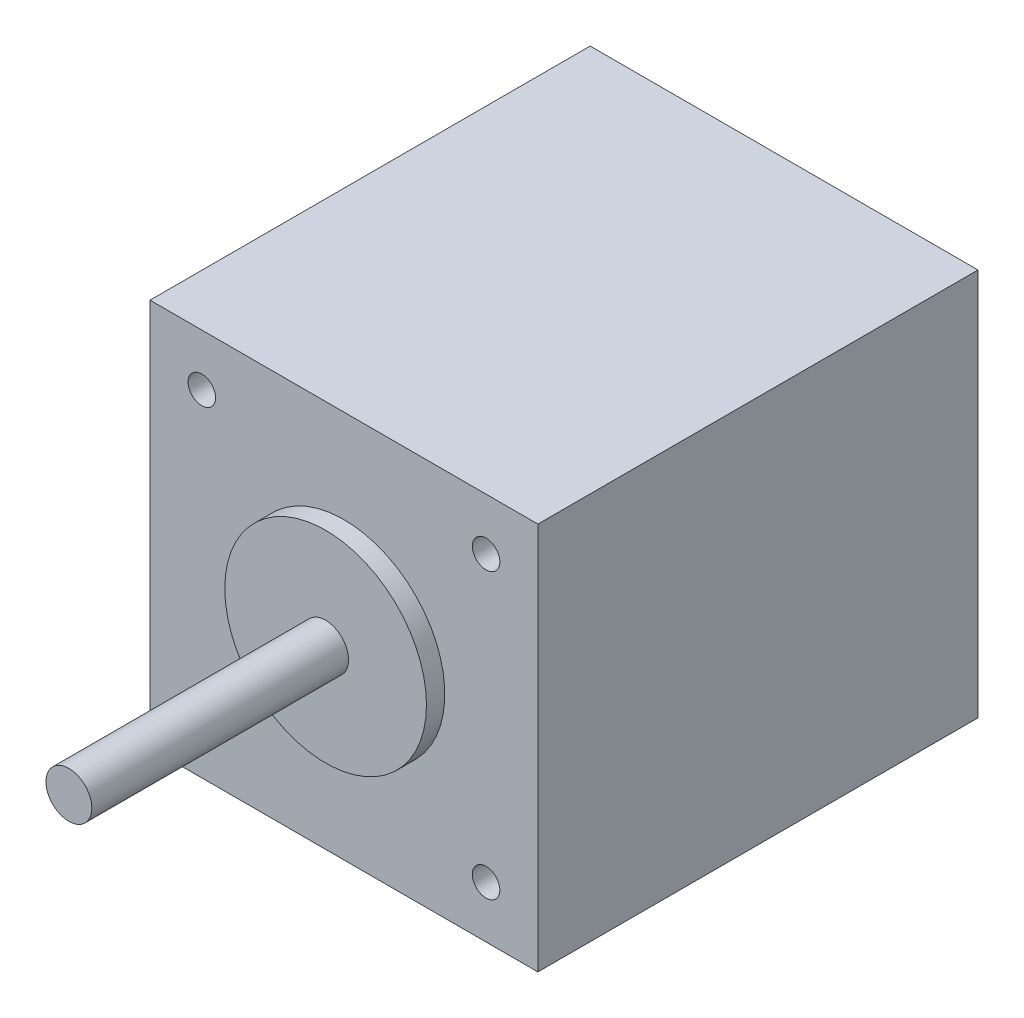
SolidWorks part; units mm, degrees
ref_plane "Спереди" through (0, 0, 0) normal (0, 0, 1) x (1, 0, 0)
ref_plane "Сверху" through (0, 0, 0) normal (0, 1, 0) x (1, 0, 0)
ref_plane "Справа" through (0, 0, 0) normal (1, 0, 0) x (0, 0, -1)
other "Configuration Table"
sketch "Эскиз1" plane through (0, 0, 0) normal (0, 0, 1) x (1, 0, 0)
  line L1 (-21.15, -21.15) -> (21.15, -21.15)
  line L2 (-21.15, -21.15) -> (-21.15, 21.15)
  line L3 (-21.15, 21.15) -> (21.15, 21.15)
  line L4 (21.15, -21.15) -> (21.15, 21.15)
  line L5 (-21.15, -21.15) -> (21.15, 21.15) construction
  line L6 (-21.15, 21.15) -> (21.15, -21.15) construction
  point P0 (0, 0)
  dimension "D1" = 42.3
  dimension "D2" = 42.3
extrude "Корпус" add sketch "Эскиз1" along normal blind 48
sketch "Эскиз2" plane through (0, 0, 0) normal (0, 0, 1) x (1, 0, 0)
  circle A0 centre (0, 0) radius 2.5
extrude "Вал_ПРЕДВ" add sketch "Эскиз2" along normal blind 78
sketch "Эскиз3" plane through (0, 0, 0) normal (0, 0, 1) x (1, 0, 0)
  circle A0 centre (0, 0) radius 11
  dimension "D1" = 22
extrude "Буртик_ПРЕДВ" add sketch "Эскиз3" along normal blind 50
sketch "Эскиз4" plane through (0, 0, 0) normal (0, 0, 1) x (1, 0, 0)
  circle A0 centre (0, 0) radius 8
  dimension "D1" = 16
sketch "Эскиз5" plane through (0, 0, 0) normal (0, 0, 1) x (1, 0, 0)
  circle A0 centre (-15.5, -15.5) radius 1.5
  circle A1 centre (-15.5, 15.5) radius 1.5
  circle A2 centre (15.5, -15.5) radius 1.5
  circle A3 centre (15.5, 15.5) radius 1.5
  dimension "D1" = 3
  dimension "D2" = 3
  dimension "D3" = 3
  dimension "D4" = 3
extrude "Крепеж_М3_ПРЕДВ" cut sketch "Эскиз5" against normal blind 4.5 from offset 48
equation "\"Мотор X ширина корпуса\"= 42.3"
equation "\"Мотор X высота корпуса\"= 42.3"
equation "\"Мотор X длина корпуса\"= 40"
equation "\"Мотор X вылет вала\"= 19.8"
equation "\"Мотор Y ширина корпуса\"= 42.3"
equation "\"Мотор Y высота корпуса\"= 42.3"
equation "\"Мотор Y длина корпуса\"= 48"
equation "\"Мотор Y вылет вала\"= 30"
equation "\"Мотор Z ширина корпуса\"= 42"
equation "\"Мотор Z высота корпуса\"= 42"
equation "\"Мотор Z длина корпуса\"= 40"
equation "\"Мотор Z вылет вала\"= 23"
equation "\"Мотор диаметр вала ПРЕДВ\"= 5"
equation "\"Мотор шаг крепления ПРЕДВ\"= 31"
equation "\"Мотор диаметр отверстий ПРЕДВ\"= 3"
equation "\"Мотор глубина отверстий ПРЕДВ\"= 4.5"
equation "\"Мотор диаметр буртика ПРЕДВ\"= 22"
equation "\"Мотор высота буртика ПРЕДВ\"= 2"
equation "\"Мотор диаметр шкива ПРЕДВ\"= 16"
equation "\"Мотор длина шкива ПРЕДВ\"= 12"
equation "\"Мотор отступ шкива ПРЕДВ\"= 5"
equation "\"Мотор X шаг градусов\"= 1.8"
equation "\"Мотор Y шаг градусов\"= 1.8"
equation "\"Мотор Z шаг градусов\"= 1.8"
equation "\"Мотор Y диаметр ротора\"= 25.78"
equation "\"D1@Эскиз1\" = \"Мотор Y ширина корпуса\""
equation "\"D1@Корпус\" = \"Мотор Y длина корпуса\""
equation "\"D1@Эскиз2\" = \"Мотор диаметр вала ПРЕДВ\""
equation "\"D1@Вал_ПРЕДВ\" = \"Мотор Y длина корпуса\" + \"Мотор Y вылет вала\""
equation "\"D1@Эскиз3\" = \"Мотор диаметр буртика ПРЕДВ\""
equation "\"D1@Буртик_ПРЕДВ\" = \"Мотор Y длина корпуса\" + \"Мотор высота буртика ПРЕДВ\""
equation "\"D1@Эскиз4\" = \"Мотор диаметр шкива ПРЕДВ\""
equation "\"D1@Эскиз5\" = \"Мотор диаметр отверстий ПРЕДВ\""
equation "\"D2@Эскиз5\" = \"Мотор диаметр отверстий ПРЕДВ\""
equation "\"D3@Эскиз5\" = \"Мотор диаметр отверстий ПРЕДВ\""
equation "\"D4@Эскиз5\" = \"Мотор диаметр отверстий ПРЕДВ\""
equation "\"D1@Крепеж_М3_ПРЕДВ\" = \"Мотор глубина отверстий ПРЕДВ\""
equation "\"D19@Крепеж_М3_ПРЕДВ\" = \"Мотор Y длина корпуса\""
equation "\"Ширина груза\"= 160"
equation "\"Глубина груза\"= 240"
equation "\"Высота груза\"= 160"
equation "\"Ширина ячейки\"= \"Ширина груза\" + 10"
equation "\"Глубина ячейки\"= \"Глубина груза\" + 10"
equation "\"Высота ячейки\"= \"Высота груза\" + 10 + 13"
equation "\"Колво ячеек ширина\"= 2"
equation "\"Колво ячеек высота\"= 2"
equation "\"Толщина стенки\"= \"Толщина тонких панелей\""
equation "\"Крепление дверцы\"= 5 "
equation "\"Ширина рейки\"= \"Толщина шестерни\""
equation "\"Высота рейки\"= 20"
equation "\"Высота пола\"= 2*\"Толщина тонких панелей\""
equation "\"Колво полозьев\"= 5"
equation "\"Отступ рейки\"= 20"
equation "\"Глубина каретки\"= \"Глубина ячейки\" + 30 + \"Мотор Y высота корпуса\" + 20"
equation "\"Отступ шпильки\"= 26"
equation "\"Диаметр шпильки\"= 5"
equation "\"Длинна шпильки\"= (\"Высота ячейки\"+\"Толщина горизонтальных плит\"+\"Высота пола\")*\"Колво ячеек высота\"+2*(\"Толщина горизонтальных плит\"+\"Отступ рейки\")"
equation "\"Ширина пластины\"= 50  "
equation "\"Высота зона выгрузки\"= \"Высота ячейки\" * 2 + \"Толщина стенки\" * 2"
equation "\"Колво выгрузки\"= 1"
equation "\"Отступ крепления мотора фиксации\"= (\"Ширина пластины\"+20-\"Толщина вертикальных стенок\")/2"
equation "\"Ширина ячейки выгрузки\"= \"Ширина ячейки\"+\"Толщина вертикальных стенок\"+2*\"Отступ крепления мотора фиксации\""
equation "\"Длинна рейки\"= (\"Ширина ячейки\"+\"Толщина вертикальных стенок\"+\"Крепление дверцы\")*\"Колво ячеек ширина\"+\"Ширина ячейки выгрузки\"*\"Колво выгрузки\"+\"Толщина вертикальных стенок\"+2*\"Отступ крепления мотора фиксации\"-\"Крепление дверцы\"*\"Колво ячеек ширина\""
equation "\"Толщина шестерни\"= 10"
equation "\"Толщина тонких панелей\"= 6"
equation "\"Толщина вертикальных стенок\"= 6"
equation "\"Толщина горизонтальных плит\"= 6"
equation "\"Базовая высота корпуса\"= (\"Высота ячейки\"+\"Толщина тонких панелей\"+\"Высота пола\")*\"Колво ячеек высота\"+6*\"Толщина тонких панелей\"+\"Мотор X ширина корпуса\"+\"Мотор Y ширина корпуса\"+75"
equation "\"Высота корпуса\"= (\"Высота ячейки\"+\"Толщина горизонтальных плит\"+\"Высота пола\")*\"Колво ячеек высота\"+2*\"Толщина горизонтальных плит\"+4*\"Толщина тонких панелей\"+\"Мотор X ширина корпуса\"+\"Мотор Y ширина корпуса\"+75"
equation "\"Смещение центра корпуса\"= (\"Высота корпуса\"-\"Базовая высота корпуса\")/2-(\"Толщина горизонтальных плит\"-\"Толщина тонких панелей\")"
equation "\"Отметка пола\"= -\"Базовая высота корпуса\"/2+\"Толщина тонких панелей\""
equation "\"Отметка потолка\"= \"Отметка пола\"+\"Высота корпуса\"-2*\"Толщина горизонтальных плит\""
equation "\"Отметка верхней полки\"= \"Отметка потолка\"-(28+\"Толщина тонких панелей\")-\"Высота ячейки\"-\"Высота пола\""
equation "\"Отметка нижней полки\"= \"Отметка верхней полки\"-\"Высота ячейки\"-\"Высота пола\"-\"Толщина горизонтальных плит\""
